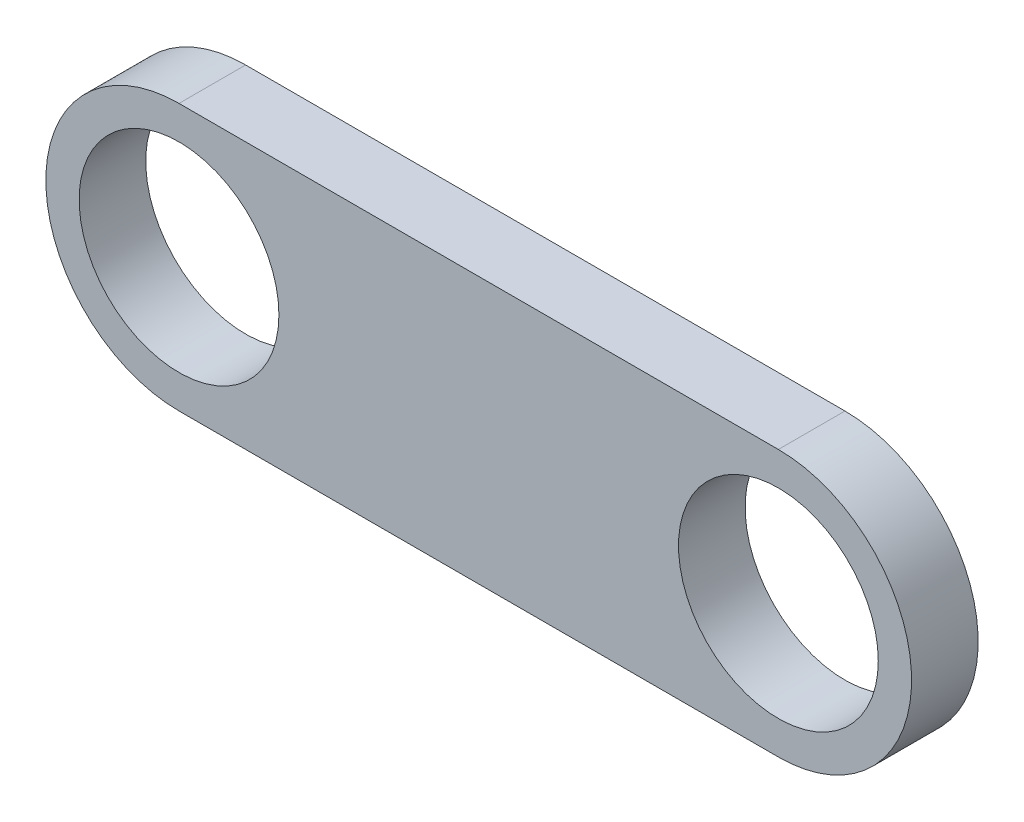
SolidWorks part; units mm, degrees
ref_plane "Спереди" through (0, 0, 0) normal (0, 0, 1) x (1, 0, 0)
ref_plane "Сверху" through (0, 0, 0) normal (0, 1, 0) x (1, 0, 0)
ref_plane "Справа" through (0, 0, 0) normal (1, 0, 0) x (0, 0, -1)
other "Configuration Table"
sketch "Эскиз1" plane through (0, 0, 0) normal (0, 0, 1) x (1, 0, 0)
  line L0 (0, 0) -> (90, 0) construction
  line L1 (0, 20) -> (90, 20)
  line L2 (0, -20) -> (90, -20)
  arc A0 (0, 20) -> (0, -20) centre (0, 0) ccw
  arc A1 (90, -20) -> (90, 20) centre (90, 0) ccw
  circle A2 centre (0, 0) radius 15
  circle A3 centre (90, 0) radius 15
  point P3 (45, 0)
  point P10 (0, 0)
  dimension "D3" = 30
  dimension "D4" = 30
  dimension "D1" = 90
  dimension "D2" = 40
extrude "Бобышка-Вытянуть2" add sketch "Эскиз1" along normal blind 10
